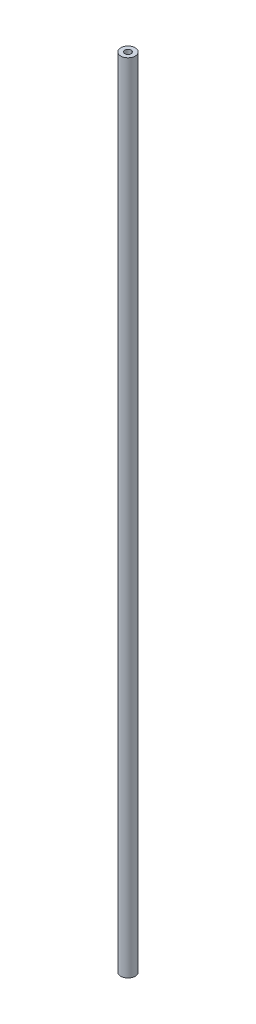
SolidWorks part; units mm, degrees
ref_plane "Front Plane" through (0, 0, 0) normal (0, 0, 1) x (1, 0, 0)
ref_plane "Top Plane" through (0, 0, 0) normal (0, 1, 0) x (1, 0, 0)
ref_plane "Right Plane" through (0, 0, 0) normal (1, 0, 0) x (0, 0, -1)
sketch "Sketch1" plane through (0, 0, 0) normal (0, 1, 0) x (1, 0, 0)
  circle A0 centre (0, 0) radius 0.25
  circle A1 centre (0, 0) radius 0.11
  dimension "D1" = 0.22
  dimension "D2" = 0.5
extrude "Boss-Extrude1" add sketch "Sketch1" along normal blind 27.57
